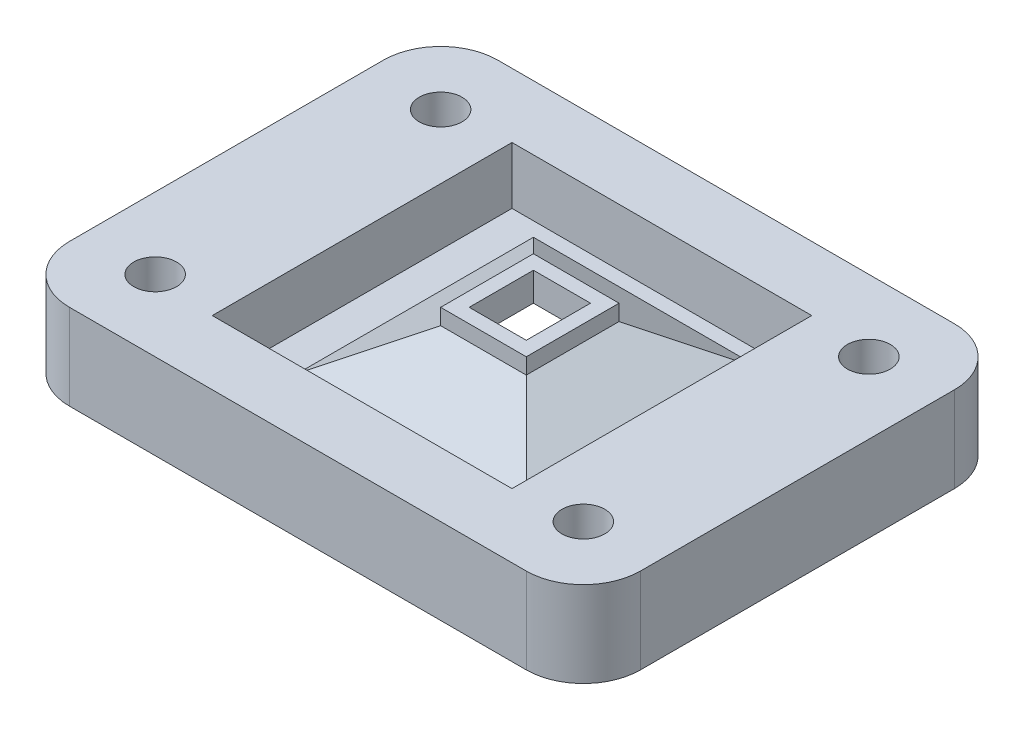
SolidWorks part; units mm, degrees
ref_plane "Front" through (0, 0, 0) normal (0, 0, 1) x (1, 0, 0)
ref_plane "Top" through (0, 0, 0) normal (0, 1, 0) x (1, 0, 0)
ref_plane "Right" through (0, 0, 0) normal (1, 0, 0) x (0, 0, -1)
sketch "Sketch1" plane through (0, 0, 0) normal (0, 1, 0) x (1, 0, 0)
  line L1 (0, 0) -> (40, 0)
  line L2 (0, 0) -> (0, 30)
  line L3 (0, 30) -> (40, 30)
  line L4 (40, 0) -> (40, 30)
  dimension "D1" = 40
  dimension "D2" = 30
extrude "Boss-Extrude1" add sketch "Sketch1" along normal blind 6
sketch "Sketch2" plane through (0, 6, 0) normal (0, 1, 0) x (1, 0, 0)
  line L0 (20, 30) -> (20, 0) construction
  line L1 (40, 30) -> (0, 30) construction
  line L2 (0, 0) -> (40, 0) construction
  line L3 (0, 15) -> (40, 15) construction
  line L4 (0, 30) -> (0, 0) construction
  line L5 (40, 0) -> (40, 30) construction
  circle A0 centre (5, 5) radius 1.5
  circle A1 centre (5, 25) radius 1.5
  circle A2 centre (35, 5) radius 1.5
  circle A3 centre (35, 25) radius 1.5
  dimension "D1" = 3
  dimension "D2" = 5
  dimension "D3" = 5
extrude "Cut-Extrude1" cut sketch "Sketch2" against normal up to surface (6 mm away) up to face at (20, 0, -15)
fillet "Fillet1" radius 4 4 edges at (0, 3, -30) (40, 3, -30) (40, 3, 0) (0, 3, 0)
sketch "Sketch3" plane through (0, 6, 0) normal (0, 1, 0) x (1, 0, 0)
  line L0 (4, 0) -> (36, 0) construction
  line L1 (9.5, 4.5) -> (30.5, 4.5)
  line L2 (9.5, 4.5) -> (9.5, 25.5)
  line L3 (9.5, 25.5) -> (30.5, 25.5)
  line L4 (30.5, 4.5) -> (30.5, 25.5)
  line L5 (0, 26) -> (0, 4) construction
  point P4 (20, 4.5)
  point P7 (20, 0)
  point P8 (9.5, 15)
  point P11 (0, 15)
  dimension "D1" = 21
  dimension "D2" = 21
extrude "Cut-Extrude2" cut sketch "Sketch3" against normal blind 4
sketch "Sketch6" plane through (0, 2, 0) normal (0, 1, 0) x (1, 0, 0)
  line L0 (9.5, 25.5) -> (9.5, 4.5) construction
  line L1 (18, 14) -> (22, 14)
  line L2 (18, 14) -> (18, 18.5)
  line L3 (18, 18.5) -> (22, 18.5)
  line L4 (22, 14) -> (22, 18.5)
  line L5 (30.5, 25.5) -> (9.5, 25.5) construction
  line L6 (30.5, 4.5) -> (30.5, 25.5) construction
  line L7 (9.5, 4.5) -> (30.5, 4.5) construction
  dimension "D1" = 8.5
  dimension "D2" = 8.5
  dimension "D3" = 9.5
  dimension "D4" = 7
extrude "Cut-Extrude3" cut sketch "Sketch6" against normal up to surface (2 mm away) up to face at (5, 0, -26.5)
sketch "Sketch7" plane through (0, 2, 0) normal (0, 1, 0) x (1, 0, 0)
  line L5 (18, 18.5) -> (22, 18.5)
  line L6 (18, 18.5) -> (18, 14)
  line L7 (18, 14) -> (22, 14)
  line L8 (17, 13) -> (23, 13)
  line L9 (23, 13) -> (23, 19.5)
  line L10 (23, 19.5) -> (17, 19.5)
  line L11 (17, 19.5) -> (17, 13)
  line L12 (17, 13) -> (23, 13)
  line L13 (23, 13) -> (23, 19.5)
  line L14 (23, 19.5) -> (17, 19.5)
  line L15 (17, 19.5) -> (17, 13)
  line L16 (22, 18.5) -> (22, 14)
  dimension "D1" = 1
extrude "Boss-Extrude2" add sketch "Sketch7" along normal blind 4
chamfer "Chamfer1" distance 4 angle 60 4 edges at (18, 0, -16.25) (20, 0, -14) (22, 0, -16.25) (20, 0, -18.5)
chamfer "Chamfer2" distance 5 angle 30 4 edges at (17, 2, -16.25) (20, 2, -19.5) (23, 2, -16.25) (20, 2, -13)
